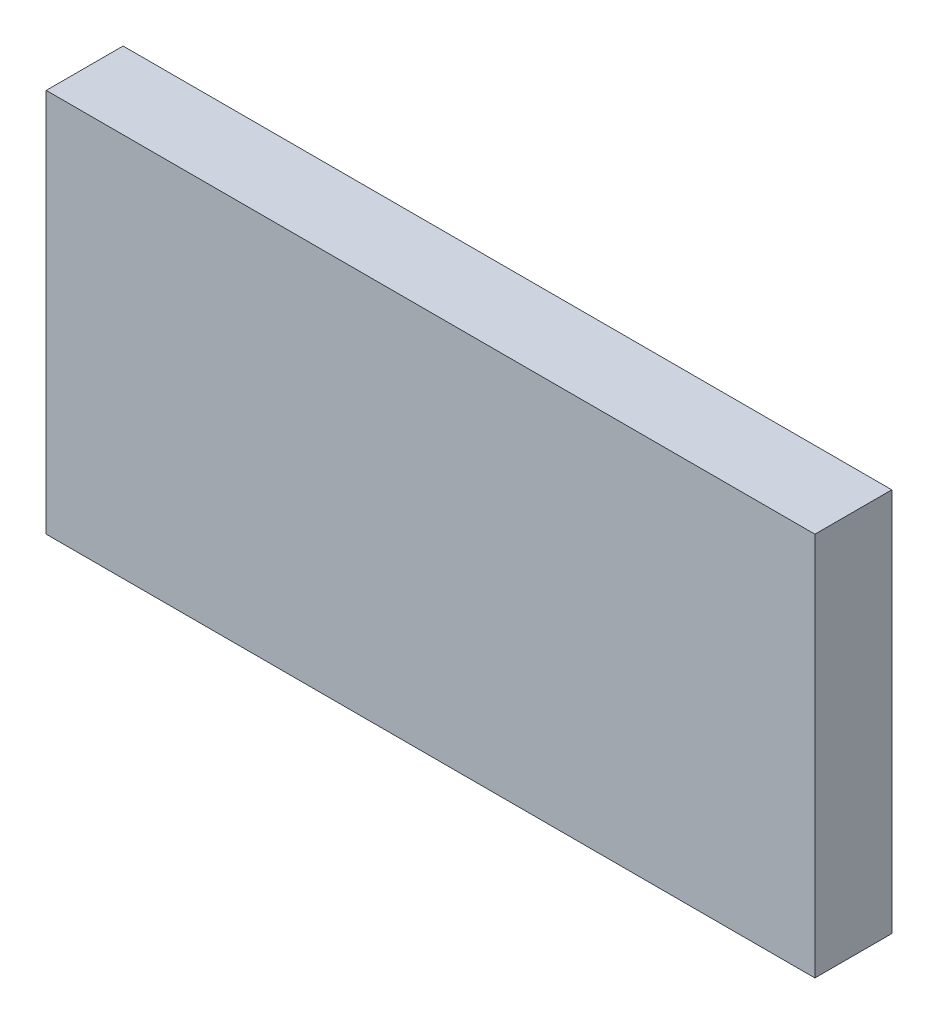
SolidWorks part; units mm, degrees
ref_plane "Front Plane" through (0, 0, 0) normal (0, 0, 1) x (1, 0, 0)
ref_plane "Top Plane" through (0, 0, 0) normal (0, 1, 0) x (1, 0, 0)
ref_plane "Right Plane" through (0, 0, 0) normal (1, 0, 0) x (0, 0, -1)
sketch "Sketch1" plane through (0, 0, 0) normal (0, 0, 1) x (1, 0, 0)
  line L1 (0, 0) -> (40, 0)
  line L2 (0, 0) -> (0, 20)
  line L3 (0, 20) -> (40, 20)
  line L4 (40, 0) -> (40, 20)
extrude "Boss-Extrude1" add sketch "Sketch1" along normal blind 4
